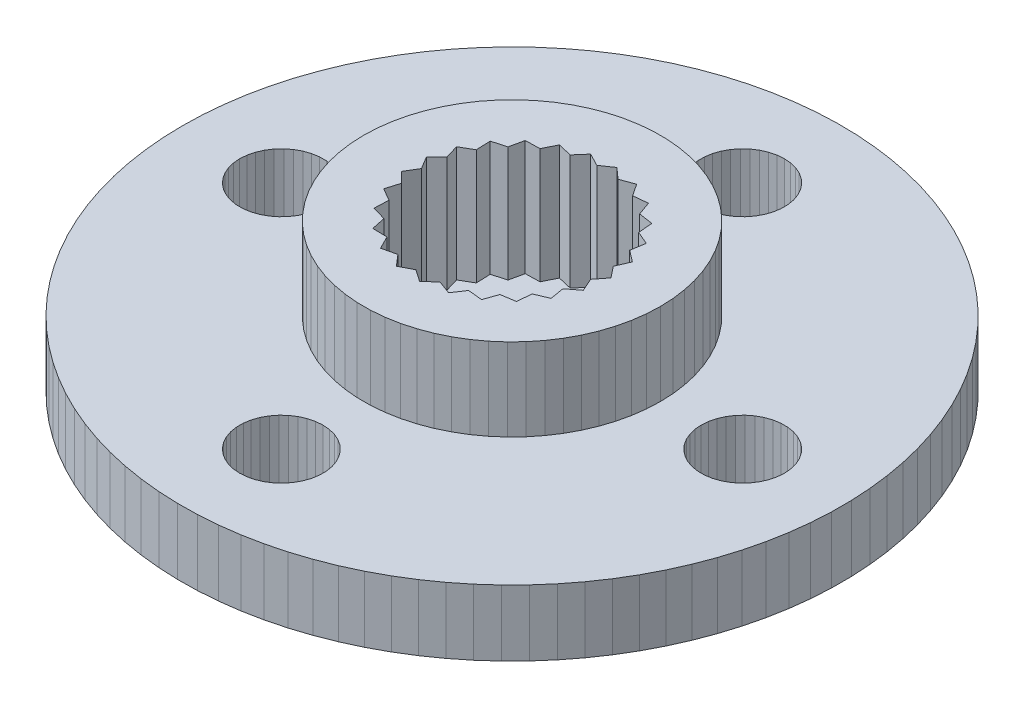
SolidWorks part; units mm, degrees
ref_plane "Front Plane" through (0, 0, 0) normal (0, 0, 1) x (1, 0, 0)
ref_plane "Top Plane" through (0, 0, 0) normal (0, 1, 0) x (1, 0, 0)
ref_plane "Right Plane" through (0, 0, 0) normal (1, 0, 0) x (0, 0, -1)
ref_plane "Plane1" through (0, 0, 0) normal (0, -1, 0) x (1, 0, 0)
sketch "Sketch1" plane through (0, 0, 0) normal (0, -1, 0) x (1, 0, 0)
  line L0 (9.9955, -0.2992) -> (9.9955, 0.2992)
  line L1 (9.9955, 0.2992) -> (9.9597, 0.8964)
  line L2 (9.9597, 0.8964) -> (9.8883, 1.4904)
  line L3 (9.8883, 1.4904) -> (9.7815, 2.0791)
  line L4 (9.7815, 2.0791) -> (9.6396, 2.6604)
  line L5 (9.6396, 2.6604) -> (9.4633, 3.2321)
  line L6 (9.4633, 3.2321) -> (9.253, 3.7923)
  line L7 (9.253, 3.7923) -> (9.0097, 4.3388)
  line L8 (9.0097, 4.3388) -> (8.7341, 4.8699)
  line L9 (8.7341, 4.8699) -> (8.4272, 5.3835)
  line L10 (8.4272, 5.3835) -> (8.0902, 5.8779)
  line L11 (8.0902, 5.8779) -> (7.7242, 6.3512)
  line L12 (7.7242, 6.3512) -> (7.3305, 6.8017)
  line L13 (7.3305, 6.8017) -> (6.9106, 7.2279)
  line L14 (6.9106, 7.2279) -> (6.466, 7.6283)
  line L15 (6.466, 7.6283) -> (5.9982, 8.0013)
  line L16 (5.9982, 8.0013) -> (5.509, 8.3457)
  line L17 (5.509, 8.3457) -> (5, 8.6603)
  line L18 (5, 8.6603) -> (4.4731, 8.9438)
  line L19 (4.4731, 8.9438) -> (3.9303, 9.1953)
  line L20 (3.9303, 9.1953) -> (3.3733, 9.4139)
  line L21 (3.3733, 9.4139) -> (2.8043, 9.5988)
  line L22 (2.8043, 9.5988) -> (2.2252, 9.7493)
  line L23 (2.2252, 9.7493) -> (1.6382, 9.8649)
  line L24 (1.6382, 9.8649) -> (1.0453, 9.9452)
  line L25 (1.0453, 9.9452) -> (0.4486, 9.9899)
  line L26 (0.4486, 9.9899) -> (-0.1496, 9.9989)
  line L27 (-0.1496, 9.9989) -> (-0.7473, 9.972)
  line L28 (-0.7473, 9.972) -> (-1.3423, 9.9095)
  line L29 (-1.3423, 9.9095) -> (-1.9326, 9.8115)
  line L30 (-1.9326, 9.8115) -> (-2.5159, 9.6783)
  line L31 (-2.5159, 9.6783) -> (-3.0902, 9.5106)
  line L32 (-3.0902, 9.5106) -> (-3.6534, 9.3087)
  line L33 (-3.6534, 9.3087) -> (-4.2036, 9.0736)
  line L34 (-4.2036, 9.0736) -> (-4.7387, 8.806)
  line L35 (-4.7387, 8.806) -> (-5.2568, 8.5068)
  line L36 (-5.2568, 8.5068) -> (-5.7562, 8.1772)
  line L37 (-5.7562, 8.1772) -> (-6.2349, 7.8183)
  line L38 (-6.2349, 7.8183) -> (-6.6913, 7.4314)
  line L39 (-6.6913, 7.4314) -> (-7.1238, 7.018)
  line L40 (-7.1238, 7.018) -> (-7.5307, 6.5794)
  line L41 (-7.5307, 6.5794) -> (-7.9107, 6.1172)
  line L42 (-7.9107, 6.1172) -> (-8.2624, 5.6332)
  line L43 (-8.2624, 5.6332) -> (-8.5845, 5.129)
  line L44 (-8.5845, 5.129) -> (-8.8759, 4.6064)
  line L45 (-8.8759, 4.6064) -> (-9.1355, 4.0674)
  line L46 (-9.1355, 4.0674) -> (-9.3623, 3.5137)
  line L47 (-9.3623, 3.5137) -> (-9.5557, 2.9476)
  line L48 (-9.5557, 2.9476) -> (-9.7149, 2.3708)
  line L49 (-9.7149, 2.3708) -> (-9.8393, 1.7856)
  line L50 (-9.8393, 1.7856) -> (-9.9285, 1.1939)
  line L51 (-9.9285, 1.1939) -> (-9.9821, 0.598)
  line L52 (-9.9821, 0.598) -> (-10, 0)
  line L53 (-10, 0) -> (-9.9821, -0.598)
  line L54 (-9.9821, -0.598) -> (-9.9285, -1.1939)
  line L55 (-9.9285, -1.1939) -> (-9.8393, -1.7856)
  line L56 (-9.8393, -1.7856) -> (-9.7149, -2.3708)
  line L57 (-9.7149, -2.3708) -> (-9.5557, -2.9476)
  line L58 (-9.5557, -2.9476) -> (-9.3623, -3.5137)
  line L59 (-9.3623, -3.5137) -> (-9.1355, -4.0674)
  line L60 (-9.1355, -4.0674) -> (-8.8759, -4.6064)
  line L61 (-8.8759, -4.6064) -> (-8.5845, -5.129)
  line L62 (-8.5845, -5.129) -> (-8.2624, -5.6332)
  line L63 (-8.2624, -5.6332) -> (-7.9107, -6.1172)
  line L64 (-7.9107, -6.1172) -> (-7.5307, -6.5794)
  line L65 (-7.5307, -6.5794) -> (-7.1238, -7.018)
  line L66 (-7.1238, -7.018) -> (-6.6913, -7.4314)
  line L67 (-6.6913, -7.4314) -> (-6.2349, -7.8183)
  line L68 (-6.2349, -7.8183) -> (-5.7562, -8.1772)
  line L69 (-5.7562, -8.1772) -> (-5.2568, -8.5068)
  line L70 (-5.2568, -8.5068) -> (-4.7387, -8.806)
  line L71 (-4.7387, -8.806) -> (-4.2036, -9.0736)
  line L72 (-4.2036, -9.0736) -> (-3.6534, -9.3087)
  line L73 (-3.6534, -9.3087) -> (-3.0902, -9.5106)
  line L74 (-3.0902, -9.5106) -> (-2.5159, -9.6783)
  line L75 (-2.5159, -9.6783) -> (-1.9326, -9.8115)
  line L76 (-1.9326, -9.8115) -> (-1.3423, -9.9095)
  line L77 (-1.3423, -9.9095) -> (-0.7473, -9.972)
  line L78 (-0.7473, -9.972) -> (-0.1496, -9.9989)
  line L79 (-0.1496, -9.9989) -> (0.4486, -9.9899)
  line L80 (0.4486, -9.9899) -> (1.0453, -9.9452)
  line L81 (1.0453, -9.9452) -> (1.6382, -9.8649)
  line L82 (1.6382, -9.8649) -> (2.2252, -9.7493)
  line L83 (2.2252, -9.7493) -> (2.8043, -9.5988)
  line L84 (2.8043, -9.5988) -> (3.3733, -9.4139)
  line L85 (3.3733, -9.4139) -> (3.9303, -9.1953)
  line L86 (3.9303, -9.1953) -> (4.4731, -8.9438)
  line L87 (4.4731, -8.9438) -> (5, -8.6603)
  line L88 (5, -8.6603) -> (5.509, -8.3457)
  line L89 (5.509, -8.3457) -> (5.9982, -8.0013)
  line L90 (5.9982, -8.0013) -> (6.466, -7.6283)
  line L91 (6.466, -7.6283) -> (6.9106, -7.2279)
  line L92 (6.9106, -7.2279) -> (7.3305, -6.8017)
  line L93 (7.3305, -6.8017) -> (7.7242, -6.3512)
  line L94 (7.7242, -6.3512) -> (8.0902, -5.8779)
  line L95 (8.0902, -5.8779) -> (8.4272, -5.3835)
  line L96 (8.4272, -5.3835) -> (8.7341, -4.8699)
  line L97 (8.7341, -4.8699) -> (9.0097, -4.3388)
  line L98 (9.0097, -4.3388) -> (9.253, -3.7923)
  line L99 (9.253, -3.7923) -> (9.4633, -3.2321)
  line L100 (9.4633, -3.2321) -> (9.6396, -2.6604)
  line L101 (9.6396, -2.6604) -> (9.7815, -2.0791)
  line L102 (9.7815, -2.0791) -> (9.8883, -1.4904)
  line L103 (9.8883, -1.4904) -> (9.9597, -0.8964)
  line L104 (9.9597, -0.8964) -> (9.9955, -0.2992)
extrude "Boss-Extrude1" add sketch "Sketch1" against normal blind 2
sketch "Sketch2" plane through (0, 2, 0) normal (0, 1, 0) x (-1, 0, 0)
  line L0 (-7.5079, 1.158) -> (-7.6916, 1.0586)
  line L1 (-7.6916, 1.0586) -> (-7.8564, 0.9303)
  line L2 (-7.8564, 0.9303) -> (-7.9979, 0.7767)
  line L3 (-7.9979, 0.7767) -> (-8.1121, 0.6018)
  line L4 (-8.1121, 0.6018) -> (-8.196, 0.4106)
  line L5 (-8.196, 0.4106) -> (-8.2473, 0.2081)
  line L6 (-8.2473, 0.2081) -> (-8.2645, 0)
  line L7 (-8.2645, 0) -> (-8.2473, -0.2081)
  line L8 (-8.2473, -0.2081) -> (-8.196, -0.4106)
  line L9 (-8.196, -0.4106) -> (-8.1121, -0.6018)
  line L10 (-8.1121, -0.6018) -> (-7.9979, -0.7767)
  line L11 (-7.9979, -0.7767) -> (-7.8564, -0.9303)
  line L12 (-7.8564, -0.9303) -> (-7.6916, -1.0586)
  line L13 (-7.6916, -1.0586) -> (-7.5079, -1.158)
  line L14 (-7.5079, -1.158) -> (-7.3104, -1.2258)
  line L15 (-7.3104, -1.2258) -> (-7.1044, -1.2602)
  line L16 (-7.1044, -1.2602) -> (-6.8956, -1.2602)
  line L17 (-6.8956, -1.2602) -> (-6.6896, -1.2258)
  line L18 (-6.6896, -1.2258) -> (-6.4921, -1.158)
  line L19 (-6.4921, -1.158) -> (-6.3084, -1.0586)
  line L20 (-6.3084, -1.0586) -> (-6.1436, -0.9303)
  line L21 (-6.1436, -0.9303) -> (-6.0021, -0.7767)
  line L22 (-6.0021, -0.7767) -> (-5.8879, -0.6018)
  line L23 (-5.8879, -0.6018) -> (-5.804, -0.4106)
  line L24 (-5.804, -0.4106) -> (-5.7527, -0.2081)
  line L25 (-5.7527, -0.2081) -> (-5.7355, 0)
  line L26 (-5.7355, 0) -> (-5.7527, 0.2081)
  line L27 (-5.7527, 0.2081) -> (-5.804, 0.4106)
  line L28 (-5.804, 0.4106) -> (-5.8879, 0.6018)
  line L29 (-5.8879, 0.6018) -> (-6.0021, 0.7767)
  line L30 (-6.0021, 0.7767) -> (-6.1436, 0.9303)
  line L31 (-6.1436, 0.9303) -> (-6.3084, 1.0586)
  line L32 (-6.3084, 1.0586) -> (-6.4921, 1.158)
  line L33 (-6.4921, 1.158) -> (-6.6896, 1.2258)
  line L34 (-6.6896, 1.2258) -> (-6.8956, 1.2602)
  line L35 (-6.8956, 1.2602) -> (-7.1044, 1.2602)
  line L36 (-7.1044, 1.2602) -> (-7.3104, 1.2258)
  line L37 (-7.3104, 1.2258) -> (-7.5079, 1.158)
extrude "Cut-Extrude1" cut sketch "Sketch2" against normal through all
sketch "Sketch3" plane through (0, 2, 0) normal (0, 1, 0) x (-1, 0, 0)
  line L0 (-0.2081, 8.2473) -> (-0.4106, 8.196)
  line L1 (-0.4106, 8.196) -> (-0.6018, 8.1121)
  line L2 (-0.6018, 8.1121) -> (-0.7767, 7.9979)
  line L3 (-0.7767, 7.9979) -> (-0.9303, 7.8564)
  line L4 (-0.9303, 7.8564) -> (-1.0586, 7.6916)
  line L5 (-1.0586, 7.6916) -> (-1.158, 7.5079)
  line L6 (-1.158, 7.5079) -> (-1.2258, 7.3104)
  line L7 (-1.2258, 7.3104) -> (-1.2602, 7.1044)
  line L8 (-1.2602, 7.1044) -> (-1.2602, 6.8956)
  line L9 (-1.2602, 6.8956) -> (-1.2258, 6.6896)
  line L10 (-1.2258, 6.6896) -> (-1.158, 6.4921)
  line L11 (-1.158, 6.4921) -> (-1.0586, 6.3084)
  line L12 (-1.0586, 6.3084) -> (-0.9303, 6.1436)
  line L13 (-0.9303, 6.1436) -> (-0.7767, 6.0021)
  line L14 (-0.7767, 6.0021) -> (-0.6018, 5.8879)
  line L15 (-0.6018, 5.8879) -> (-0.4106, 5.804)
  line L16 (-0.4106, 5.804) -> (-0.2081, 5.7527)
  line L17 (-0.2081, 5.7527) -> (0, 5.7355)
  line L18 (0, 5.7355) -> (0.2081, 5.7527)
  line L19 (0.2081, 5.7527) -> (0.4106, 5.804)
  line L20 (0.4106, 5.804) -> (0.6018, 5.8879)
  line L21 (0.6018, 5.8879) -> (0.7767, 6.0021)
  line L22 (0.7767, 6.0021) -> (0.9303, 6.1436)
  line L23 (0.9303, 6.1436) -> (1.0586, 6.3084)
  line L24 (1.0586, 6.3084) -> (1.158, 6.4921)
  line L25 (1.158, 6.4921) -> (1.2258, 6.6896)
  line L26 (1.2258, 6.6896) -> (1.2602, 6.8956)
  line L27 (1.2602, 6.8956) -> (1.2602, 7.1044)
  line L28 (1.2602, 7.1044) -> (1.2258, 7.3104)
  line L29 (1.2258, 7.3104) -> (1.158, 7.5079)
  line L30 (1.158, 7.5079) -> (1.0586, 7.6916)
  line L31 (1.0586, 7.6916) -> (0.9303, 7.8564)
  line L32 (0.9303, 7.8564) -> (0.7767, 7.9979)
  line L33 (0.7767, 7.9979) -> (0.6018, 8.1121)
  line L34 (0.6018, 8.1121) -> (0.4106, 8.196)
  line L35 (0.4106, 8.196) -> (0.2081, 8.2473)
  line L36 (0.2081, 8.2473) -> (0, 8.2645)
  line L37 (0, 8.2645) -> (-0.2081, 8.2473)
extrude "Cut-Extrude2" cut sketch "Sketch3" against normal through all
sketch "Sketch4" plane through (0, 2, 0) normal (0, 1, 0) x (-1, 0, 0)
  line L0 (6.6896, 1.2258) -> (6.4921, 1.158)
  line L1 (6.4921, 1.158) -> (6.3084, 1.0586)
  line L2 (6.3084, 1.0586) -> (6.1436, 0.9303)
  line L3 (6.1436, 0.9303) -> (6.0021, 0.7767)
  line L4 (6.0021, 0.7767) -> (5.8879, 0.6018)
  line L5 (5.8879, 0.6018) -> (5.804, 0.4106)
  line L6 (5.804, 0.4106) -> (5.7527, 0.2081)
  line L7 (5.7527, 0.2081) -> (5.7355, 0)
  line L8 (5.7355, 0) -> (5.7527, -0.2081)
  line L9 (5.7527, -0.2081) -> (5.804, -0.4106)
  line L10 (5.804, -0.4106) -> (5.8879, -0.6018)
  line L11 (5.8879, -0.6018) -> (6.0021, -0.7767)
  line L12 (6.0021, -0.7767) -> (6.1436, -0.9303)
  line L13 (6.1436, -0.9303) -> (6.3084, -1.0586)
  line L14 (6.3084, -1.0586) -> (6.4921, -1.158)
  line L15 (6.4921, -1.158) -> (6.6896, -1.2258)
  line L16 (6.6896, -1.2258) -> (6.8956, -1.2602)
  line L17 (6.8956, -1.2602) -> (7.1044, -1.2602)
  line L18 (7.1044, -1.2602) -> (7.3104, -1.2258)
  line L19 (7.3104, -1.2258) -> (7.5079, -1.158)
  line L20 (7.5079, -1.158) -> (7.6916, -1.0586)
  line L21 (7.6916, -1.0586) -> (7.8564, -0.9303)
  line L22 (7.8564, -0.9303) -> (7.9979, -0.7767)
  line L23 (7.9979, -0.7767) -> (8.1121, -0.6018)
  line L24 (8.1121, -0.6018) -> (8.196, -0.4106)
  line L25 (8.196, -0.4106) -> (8.2473, -0.2081)
  line L26 (8.2473, -0.2081) -> (8.2645, 0)
  line L27 (8.2645, 0) -> (8.2473, 0.2081)
  line L28 (8.2473, 0.2081) -> (8.196, 0.4106)
  line L29 (8.196, 0.4106) -> (8.1121, 0.6018)
  line L30 (8.1121, 0.6018) -> (7.9979, 0.7767)
  line L31 (7.9979, 0.7767) -> (7.8564, 0.9303)
  line L32 (7.8564, 0.9303) -> (7.6916, 1.0586)
  line L33 (7.6916, 1.0586) -> (7.5079, 1.158)
  line L34 (7.5079, 1.158) -> (7.3104, 1.2258)
  line L35 (7.3104, 1.2258) -> (7.1044, 1.2602)
  line L36 (7.1044, 1.2602) -> (6.8956, 1.2602)
  line L37 (6.8956, 1.2602) -> (6.6896, 1.2258)
extrude "Cut-Extrude3" cut sketch "Sketch4" against normal through all
sketch "Sketch5" plane through (0, 0, 0) normal (0, -1, 0) x (1, 0, 0)
  line L0 (0, -5.7355) -> (-0.2081, -5.7527)
  line L1 (-0.2081, -5.7527) -> (-0.4106, -5.804)
  line L2 (-0.4106, -5.804) -> (-0.6018, -5.8879)
  line L3 (-0.6018, -5.8879) -> (-0.7767, -6.0021)
  line L4 (-0.7767, -6.0021) -> (-0.9303, -6.1436)
  line L5 (-0.9303, -6.1436) -> (-1.0586, -6.3084)
  line L6 (-1.0586, -6.3084) -> (-1.158, -6.4921)
  line L7 (-1.158, -6.4921) -> (-1.2258, -6.6896)
  line L8 (-1.2258, -6.6896) -> (-1.2602, -6.8956)
  line L9 (-1.2602, -6.8956) -> (-1.2602, -7.1044)
  line L10 (-1.2602, -7.1044) -> (-1.2258, -7.3104)
  line L11 (-1.2258, -7.3104) -> (-1.158, -7.5079)
  line L12 (-1.158, -7.5079) -> (-1.0586, -7.6916)
  line L13 (-1.0586, -7.6916) -> (-0.9303, -7.8564)
  line L14 (-0.9303, -7.8564) -> (-0.7767, -7.9979)
  line L15 (-0.7767, -7.9979) -> (-0.6018, -8.1121)
  line L16 (-0.6018, -8.1121) -> (-0.4106, -8.196)
  line L17 (-0.4106, -8.196) -> (-0.2081, -8.2473)
  line L18 (-0.2081, -8.2473) -> (0, -8.2645)
  line L19 (0, -8.2645) -> (0.2081, -8.2473)
  line L20 (0.2081, -8.2473) -> (0.4106, -8.196)
  line L21 (0.4106, -8.196) -> (0.6018, -8.1121)
  line L22 (0.6018, -8.1121) -> (0.7767, -7.9979)
  line L23 (0.7767, -7.9979) -> (0.9303, -7.8564)
  line L24 (0.9303, -7.8564) -> (1.0586, -7.6916)
  line L25 (1.0586, -7.6916) -> (1.158, -7.5079)
  line L26 (1.158, -7.5079) -> (1.2258, -7.3104)
  line L27 (1.2258, -7.3104) -> (1.2602, -7.1044)
  line L28 (1.2602, -7.1044) -> (1.2602, -6.8956)
  line L29 (1.2602, -6.8956) -> (1.2258, -6.6896)
  line L30 (1.2258, -6.6896) -> (1.158, -6.4921)
  line L31 (1.158, -6.4921) -> (1.0586, -6.3084)
  line L32 (1.0586, -6.3084) -> (0.9303, -6.1436)
  line L33 (0.9303, -6.1436) -> (0.7767, -6.0021)
  line L34 (0.7767, -6.0021) -> (0.6018, -5.8879)
  line L35 (0.6018, -5.8879) -> (0.4106, -5.804)
  line L36 (0.4106, -5.804) -> (0.2081, -5.7527)
  line L37 (0.2081, -5.7527) -> (0, -5.7355)
extrude "Cut-Extrude4" cut sketch "Sketch5" against normal through all
sketch "Sketch6" plane through (0, 2, 0) normal (0, 1, 0) x (-1, 0, 0)
  line L0 (-4.4819, -0.4034) -> (-4.5, 0)
  line L1 (-4.5, 0) -> (-4.4819, 0.4034)
  line L2 (-4.4819, 0.4034) -> (-4.4277, 0.8035)
  line L3 (-4.4277, 0.8035) -> (-4.3378, 1.1972)
  line L4 (-4.3378, 1.1972) -> (-4.2131, 1.5812)
  line L5 (-4.2131, 1.5812) -> (-4.0544, 1.9525)
  line L6 (-4.0544, 1.9525) -> (-3.863, 2.308)
  line L7 (-3.863, 2.308) -> (-3.6406, 2.645)
  line L8 (-3.6406, 2.645) -> (-3.3888, 2.9607)
  line L9 (-3.3888, 2.9607) -> (-3.1098, 3.2526)
  line L10 (-3.1098, 3.2526) -> (-2.8057, 3.5182)
  line L11 (-2.8057, 3.5182) -> (-2.479, 3.7556)
  line L12 (-2.479, 3.7556) -> (-2.1324, 3.9627)
  line L13 (-2.1324, 3.9627) -> (-1.7686, 4.1379)
  line L14 (-1.7686, 4.1379) -> (-1.3906, 4.2798)
  line L15 (-1.3906, 4.2798) -> (-1.0013, 4.3872)
  line L16 (-1.0013, 4.3872) -> (-0.604, 4.4593)
  line L17 (-0.604, 4.4593) -> (-0.2019, 4.4955)
  line L18 (-0.2019, 4.4955) -> (0.2019, 4.4955)
  line L19 (0.2019, 4.4955) -> (0.604, 4.4593)
  line L20 (0.604, 4.4593) -> (1.0013, 4.3872)
  line L21 (1.0013, 4.3872) -> (1.3906, 4.2798)
  line L22 (1.3906, 4.2798) -> (1.7686, 4.1379)
  line L23 (1.7686, 4.1379) -> (2.1324, 3.9627)
  line L24 (2.1324, 3.9627) -> (2.479, 3.7556)
  line L25 (2.479, 3.7556) -> (2.8057, 3.5182)
  line L26 (2.8057, 3.5182) -> (3.1098, 3.2526)
  line L27 (3.1098, 3.2526) -> (3.3888, 2.9607)
  line L28 (3.3888, 2.9607) -> (3.6406, 2.645)
  line L29 (3.6406, 2.645) -> (3.863, 2.308)
  line L30 (3.863, 2.308) -> (4.0544, 1.9525)
  line L31 (4.0544, 1.9525) -> (4.2131, 1.5812)
  line L32 (4.2131, 1.5812) -> (4.3378, 1.1972)
  line L33 (4.3378, 1.1972) -> (4.4277, 0.8035)
  line L34 (4.4277, 0.8035) -> (4.4819, 0.4034)
  line L35 (4.4819, 0.4034) -> (4.5, 0)
  line L36 (4.5, 0) -> (4.4819, -0.4034)
  line L37 (4.4819, -0.4034) -> (4.4277, -0.8035)
  line L38 (4.4277, -0.8035) -> (4.3378, -1.1972)
  line L39 (4.3378, -1.1972) -> (4.2131, -1.5812)
  line L40 (4.2131, -1.5812) -> (4.0544, -1.9525)
  line L41 (4.0544, -1.9525) -> (3.863, -2.308)
  line L42 (3.863, -2.308) -> (3.6406, -2.645)
  line L43 (3.6406, -2.645) -> (3.3888, -2.9607)
  line L44 (3.3888, -2.9607) -> (3.1098, -3.2526)
  line L45 (3.1098, -3.2526) -> (2.8057, -3.5182)
  line L46 (2.8057, -3.5182) -> (2.479, -3.7556)
  line L47 (2.479, -3.7556) -> (2.1324, -3.9627)
  line L48 (2.1324, -3.9627) -> (1.7686, -4.1379)
  line L49 (1.7686, -4.1379) -> (1.3906, -4.2798)
  line L50 (1.3906, -4.2798) -> (1.0013, -4.3872)
  line L51 (1.0013, -4.3872) -> (0.604, -4.4593)
  line L52 (0.604, -4.4593) -> (0.2019, -4.4955)
  line L53 (0.2019, -4.4955) -> (-0.2019, -4.4955)
  line L54 (-0.2019, -4.4955) -> (-0.604, -4.4593)
  line L55 (-0.604, -4.4593) -> (-1.0013, -4.3872)
  line L56 (-1.0013, -4.3872) -> (-1.3906, -4.2798)
  line L57 (-1.3906, -4.2798) -> (-1.7686, -4.1379)
  line L58 (-1.7686, -4.1379) -> (-2.1324, -3.9627)
  line L59 (-2.1324, -3.9627) -> (-2.479, -3.7556)
  line L60 (-2.479, -3.7556) -> (-2.8057, -3.5182)
  line L61 (-2.8057, -3.5182) -> (-3.1098, -3.2526)
  line L62 (-3.1098, -3.2526) -> (-3.3888, -2.9607)
  line L63 (-3.3888, -2.9607) -> (-3.6406, -2.645)
  line L64 (-3.6406, -2.645) -> (-3.863, -2.308)
  line L65 (-3.863, -2.308) -> (-4.0544, -1.9525)
  line L66 (-4.0544, -1.9525) -> (-4.2131, -1.5812)
  line L67 (-4.2131, -1.5812) -> (-4.3378, -1.1972)
  line L68 (-4.3378, -1.1972) -> (-4.4277, -0.8035)
  line L69 (-4.4277, -0.8035) -> (-4.4819, -0.4034)
extrude "Boss-Extrude2" add sketch "Sketch6" along normal blind 2.5
sketch "Sketch7" plane through (0, 4.5, 0) normal (0, 1, 0) x (-1, 0, 0)
  line L0 (-2.7283, 0.3447) -> (-3, 0)
  line L1 (-3, 0) -> (-2.7283, -0.3447)
  line L2 (-2.7283, -0.3447) -> (-2.9057, -0.7461)
  line L3 (-2.9057, -0.7461) -> (-2.5569, -1.0123)
  line L4 (-2.5569, -1.0123) -> (-2.6289, -1.4453)
  line L5 (-2.6289, -1.4453) -> (-2.2248, -1.6164)
  line L6 (-2.2248, -1.6164) -> (-2.1869, -2.0536)
  line L7 (-2.1869, -2.0536) -> (-1.7529, -2.1189)
  line L8 (-1.7529, -2.1189) -> (-1.6075, -2.533)
  line L9 (-1.6075, -2.533) -> (-1.1709, -2.4883)
  line L10 (-1.1709, -2.4883) -> (-0.9271, -2.8532)
  line L11 (-0.9271, -2.8532) -> (-0.5153, -2.7013)
  line L12 (-0.5153, -2.7013) -> (-0.1884, -2.9941)
  line L13 (-0.1884, -2.9941) -> (0.1727, -2.7446)
  line L14 (0.1727, -2.7446) -> (0.5621, -2.9469)
  line L15 (0.5621, -2.9469) -> (0.8498, -2.6154)
  line L16 (0.8498, -2.6154) -> (1.2773, -2.7145)
  line L17 (1.2773, -2.7145) -> (1.4735, -2.3219)
  line L18 (1.4735, -2.3219) -> (1.9123, -2.3115)
  line L19 (1.9123, -2.3115) -> (2.0047, -1.8825)
  line L20 (2.0047, -1.8825) -> (2.4271, -1.7634)
  line L21 (2.4271, -1.7634) -> (2.4098, -1.3248)
  line L22 (2.4098, -1.3248) -> (2.7893, -1.1044)
  line L23 (2.7893, -1.1044) -> (2.6636, -0.6839)
  line L24 (2.6636, -0.6839) -> (2.9763, -0.376)
  line L25 (2.9763, -0.376) -> (2.75, 0)
  line L26 (2.75, 0) -> (2.9763, 0.376)
  line L27 (2.9763, 0.376) -> (2.6636, 0.6839)
  line L28 (2.6636, 0.6839) -> (2.7893, 1.1044)
  line L29 (2.7893, 1.1044) -> (2.4098, 1.3248)
  line L30 (2.4098, 1.3248) -> (2.4271, 1.7634)
  line L31 (2.4271, 1.7634) -> (2.0047, 1.8825)
  line L32 (2.0047, 1.8825) -> (1.9123, 2.3115)
  line L33 (1.9123, 2.3115) -> (1.4735, 2.3219)
  line L34 (1.4735, 2.3219) -> (1.2773, 2.7145)
  line L35 (1.2773, 2.7145) -> (0.8498, 2.6154)
  line L36 (0.8498, 2.6154) -> (0.5621, 2.9469)
  line L37 (0.5621, 2.9469) -> (0.1727, 2.7446)
  line L38 (0.1727, 2.7446) -> (-0.1884, 2.9941)
  line L39 (-0.1884, 2.9941) -> (-0.5153, 2.7013)
  line L40 (-0.5153, 2.7013) -> (-0.9271, 2.8532)
  line L41 (-0.9271, 2.8532) -> (-1.1709, 2.4883)
  line L42 (-1.1709, 2.4883) -> (-1.6075, 2.533)
  line L43 (-1.6075, 2.533) -> (-1.7529, 2.1189)
  line L44 (-1.7529, 2.1189) -> (-2.1869, 2.0536)
  line L45 (-2.1869, 2.0536) -> (-2.2248, 1.6164)
  line L46 (-2.2248, 1.6164) -> (-2.6289, 1.4453)
  line L47 (-2.6289, 1.4453) -> (-2.5569, 1.0123)
  line L48 (-2.5569, 1.0123) -> (-2.9057, 0.7461)
  line L49 (-2.9057, 0.7461) -> (-2.7283, 0.3447)
extrude "Cut-Extrude5" cut sketch "Sketch7" against normal blind 3.5
sketch "Sketch8" plane through (0, 1, 0) normal (0, 1, 0) x (-1, 0, 0)
  line L0 (-1.4605, -0.3418) -> (-1.3913, -0.5607)
  line L1 (-1.3913, -0.5607) -> (-1.2894, -0.7665)
  line L2 (-1.2894, -0.7665) -> (-1.1572, -0.9544)
  line L3 (-1.1572, -0.9544) -> (-0.998, -1.1198)
  line L4 (-0.998, -1.1198) -> (-0.8154, -1.259)
  line L5 (-0.8154, -1.259) -> (-0.6136, -1.3688)
  line L6 (-0.6136, -1.3688) -> (-0.3975, -1.4464)
  line L7 (-0.3975, -1.4464) -> (-0.172, -1.4901)
  line L8 (-0.172, -1.4901) -> (0.0575, -1.4989)
  line L9 (0.0575, -1.4989) -> (0.2856, -1.4726)
  line L10 (0.2856, -1.4726) -> (0.507, -1.4117)
  line L11 (0.507, -1.4117) -> (0.7166, -1.3178)
  line L12 (0.7166, -1.3178) -> (0.9093, -1.1929)
  line L13 (0.9093, -1.1929) -> (1.0808, -1.0401)
  line L14 (1.0808, -1.0401) -> (1.2269, -0.863)
  line L15 (1.2269, -0.863) -> (1.3442, -0.6656)
  line L16 (1.3442, -0.6656) -> (1.4301, -0.4526)
  line L17 (1.4301, -0.4526) -> (1.4824, -0.229)
  line L18 (1.4824, -0.229) -> (1.5, 0)
  line L19 (1.5, 0) -> (1.4824, 0.229)
  line L20 (1.4824, 0.229) -> (1.4301, 0.4526)
  line L21 (1.4301, 0.4526) -> (1.3442, 0.6656)
  line L22 (1.3442, 0.6656) -> (1.2269, 0.863)
  line L23 (1.2269, 0.863) -> (1.0808, 1.0401)
  line L24 (1.0808, 1.0401) -> (0.9093, 1.1929)
  line L25 (0.9093, 1.1929) -> (0.7166, 1.3178)
  line L26 (0.7166, 1.3178) -> (0.507, 1.4117)
  line L27 (0.507, 1.4117) -> (0.2856, 1.4726)
  line L28 (0.2856, 1.4726) -> (0.0575, 1.4989)
  line L29 (0.0575, 1.4989) -> (-0.172, 1.4901)
  line L30 (-0.172, 1.4901) -> (-0.3975, 1.4464)
  line L31 (-0.3975, 1.4464) -> (-0.6136, 1.3688)
  line L32 (-0.6136, 1.3688) -> (-0.8154, 1.259)
  line L33 (-0.8154, 1.259) -> (-0.998, 1.1198)
  line L34 (-0.998, 1.1198) -> (-1.1572, 0.9544)
  line L35 (-1.1572, 0.9544) -> (-1.2894, 0.7665)
  line L36 (-1.2894, 0.7665) -> (-1.3913, 0.5607)
  line L37 (-1.3913, 0.5607) -> (-1.4605, 0.3418)
  line L38 (-1.4605, 0.3418) -> (-1.4956, 0.1148)
  line L39 (-1.4956, 0.1148) -> (-1.4956, -0.1148)
  line L40 (-1.4956, -0.1148) -> (-1.4605, -0.3418)
extrude "Cut-Extrude6" cut sketch "Sketch8" against normal through all
